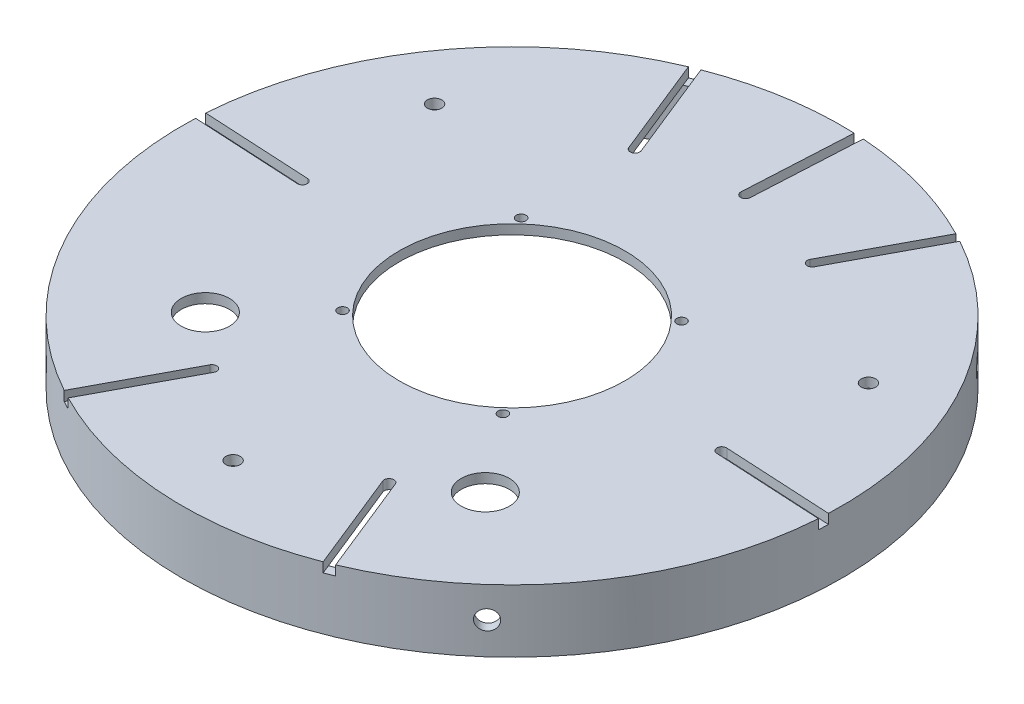
SolidWorks part; units mm, degrees
material "6061 Alloy"
ref_plane "Front Plane" through (0, 0, 0) normal (0, 0, 1) x (1, 0, 0)
ref_plane "Top Plane" through (0, 0, 0) normal (0, 1, 0) x (1, 0, 0)
ref_plane "Right Plane" through (0, 0, 0) normal (1, 0, 0) x (0, 0, -1)
sketch "Sketch1" plane through (0, 0, 0) normal (0, 1, 0) x (-0.9986, 0, -0.0535)
  line L0 (55.4987, 41.0091) -> (55.4987, 34.0091) construction
  line L2 (55.4987, -32.3449) -> (55.4987, -2.3278) construction
  circle A1 centre (55.4987, -32.3449) radius 68.37
  circle A3 centre (55.4987, -32.3449) radius 23.401
extrude "Boss-Extrude1" add sketch "Sketch1" along normal blind 2
sketch "Sketch3" plane through (0, 2, 0) normal (0, 1, 0) x (1, 0, 0)
  circle A0 centre (-53.6871, 35.2703) radius 68.37
  circle A1 centre (-53.6871, 35.2703) radius 66.37
extrude "Boss-Extrude2" add sketch "Sketch3" against normal blind 13
sketch "Sketch24" [suppressed] plane through (0, 4.3, 0) normal (0, 1, 0) x (1, 0, 0)
  line L0 (-34.4111, 2.0274) -> (-34.9466, -7.9582) construction
  line L1 (25.902, -11.2211) -> (26.4375, -1.2355) construction
  point P0 (-34.6788, -2.9654)
  point P1 (26.1698, -6.2283)
sketch "Sketch25" [suppressed] plane through (0, 0, 0) normal (0, -1, 0) x (1, 0, 0)
  point P0 (-34.6788, 2.9654)
  point P1 (26.1698, 6.2283)
ref_plane "Plane1" [suppressed] through (-0.258, 0, 4.8112) normal (0.0535, 0, -0.9986) x (-0.9986, 0, -0.0535)
sketch "Sketch29" [suppressed] plane through (0, 4.3, 0) normal (0, 1, 0) x (1, 0, 0)
  arc A0 (18.841, -0.8281) -> (-26.8146, 1.6201) centre (-4.2545, -4.5968) ccw construction
  arc A1 (-27.3501, -8.3656) -> (18.3055, -10.8138) centre (-4.2545, -4.5968) ccw construction
  point P0 (-3.0015, 18.7706)
  point P1 (-5.5076, -27.9643)
sketch "Sketch30" [suppressed] plane through (0, 0, 0) normal (0, -1, 0) x (1, 0, 0)
  point P0 (-5.5076, 27.9643)
  point P1 (-3.0015, -18.7706)
ref_plane "Plane2" [suppressed] through (-3.9965, 0, -0.2143) normal (-0.9986, 0, -0.0535) x (-0.0535, 0, 0.9986)
sketch "Sketch35" [suppressed] plane through (0, 0, 0) normal (0, 1, 0) x (1, 0, 0)
  line L0 (-3.8699, 2.5759) -> (-4.1232, -2.1473) construction
  line L1 (2.1036, -4.9378) -> (-2.6196, -4.6845) construction
  line L2 (20.5267, 17.662) -> (-4.2545, -4.5968) construction
  line L3 (-4.2545, -4.5968) -> (-31.1135, -28.7219) construction
  arc A1 (-27.3501, -8.3656) -> (18.3055, -10.8138) centre (-4.2545, -4.5968) ccw construction
  point P0 (-4.2545, -4.5968)
  point P8 (20.5267, 17.662)
  point P10 (-21.6638, -20.2341)
sketch "Sketch36" [suppressed] plane through (0, 4.3, 0) normal (0, 1, 0) x (1, 0, 0)
  point P0 (20.5267, 17.662)
ref_plane "Plane3" [suppressed] through (0.3855, 0, 0.4291) normal (0.6682, 0, 0.744) x (0.744, 0, -0.6682)
sketch "Sketch37" [suppressed] plane through (0, 4.3, 0) normal (0, 1, 0) x (1, 0, 0)
  line L1 (-26.6296, 20.3138) -> (-4.2545, -4.5968) construction
  line L2 (-4.2545, -4.5968) -> (20.7564, -32.4421) construction
  point P0 (-4.2545, -4.5968)
  point P7 (-26.6296, 20.3138)
sketch "Sketch39" [suppressed] plane through (0, 0, 0) normal (0, -1, 0) x (1, 0, 0)
  point P0 (-26.6296, -20.3138)
ref_plane "Plane4" [suppressed] through (-4.64, 0, 4.1677) normal (-0.744, 0, 0.6682) x (0.6682, 0, 0.744)
sketch "Sketch40" [suppressed] plane through (0.3855, 0, 0.4291) normal (0.6682, 0, 0.744) x (0.744, 0, -0.6682)
  circle A0 centre (-6.2369, -3.85) radius 2
extrude "Cut-Extrude27" [suppressed] cut sketch "Sketch40" against normal through all
pattern_circular "CirPattern2" [suppressed] count 4 over 360
sketch "Sketch58" plane through (0, 2, 0) normal (0, 1, 0) x (1, 0, 0)
  line L2 (-12.7238, 29.0656) -> (-12.2954, 37.0565)
  line L3 (-12.2954, 37.0565) -> (-7.3025, 36.7887)
  line L4 (-7.3025, 36.7887) -> (-7.731, 28.7979)
  line L5 (-7.731, 28.7979) -> (-12.7238, 29.0656)
sketch "Sketch60" plane through (0, 2, 0) normal (0, 1, 0) x (1, 0, 0)
  line L0 (-52.2437, 62.1872) -> (-55.1305, 8.3534) construction
  line L1 (-84.1539, 36.904) -> (-23.2203, 33.6365) construction
  line L4 (-73.7408, 17.2578) -> (-104.5394, -10.4059) construction
  line L5 (-53.6871, 35.2703) -> (-73.7408, 17.2578) construction
  line L6 (-71.6996, 55.324) -> (-99.3633, 86.1226) construction
  line L7 (-53.6871, 35.2703) -> (-71.6996, 55.324) construction
  line L8 (-33.6334, 53.2828) -> (-2.8348, 80.9464) construction
  line L9 (-53.6871, 35.2703) -> (-33.6334, 53.2828) construction
  line L10 (-35.6746, 15.2165) -> (-8.0109, -15.5821) construction
  line L11 (-53.6871, 35.2703) -> (-35.6746, 15.2165) construction
  line L12 (-73.7408, 17.2578) -> (-104.5394, -10.4059) construction
  line L13 (-53.6871, 35.2703) -> (-73.7408, 17.2578) construction
  arc A1 (-55.1305, 8.3534) -> (-80.604, 36.7136) centre (-53.6871, 35.2703) cw
  dimension "D1" = 4
sketch "Sketch62" plane through (0, 0, 0) normal (0, -1, 0) x (1, 0, 0)
  line L0 (-8.0109, 15.5821) -> (-99.3633, -86.1226) construction
  line L1 (-104.5394, 10.4059) -> (-2.8348, -80.9464) construction
  point P9 (-53.6871, -35.2703)
ref_plane "Plane5" through (-41.5069, 0, -46.2106) normal (0.6682, 0, 0.744) x (0.744, 0, -0.6682)
ref_plane "Plane6" through (-12.1802, 0, 10.9404) normal (0.744, 0, -0.6682) x (-0.6682, 0, -0.744)
sketch "Sketch63" plane through (-41.5069, 0, -46.2106) normal (0.6682, 0, 0.744) x (0.744, 0, -0.6682)
  line L0 (-84.7262, 0) -> (51.9818, 0) construction
  line L3 (-16.3722, 0) -> (-16.3722, -8.7) construction
  circle A0 centre (-16.3722, -4.35) radius 2
extrude "Cut-Extrude40" cut sketch "Sketch63" against normal through all and the other way through all
sketch "Sketch64" plane through (-12.1802, 0, 10.9404) normal (0.744, 0, -0.6682) x (-0.6682, 0, -0.744)
  line L0 (-6.2392, 0) -> (130.4688, 0) construction
  line L3 (62.1148, 0) -> (62.1148, -8.7) construction
  circle A0 centre (62.1148, -4.35) radius 2
extrude "Cut-Extrude41" cut sketch "Sketch64" against normal through all and the other way through all
sketch "Sketch65" plane through (0, 2, 0) normal (0, -1, 0) x (1, 0, 0)
  line L2 (1.1947, -31.5296) -> (-6.7555, -31.9265)
  line L3 (0.4048, -1118.9656) -> (-50.8954, -91.2006) construction
  line L4 (1.2944, -33.5271) -> (-6.7555, -33.9289)
  line L5 (-108.5689, -39.0109) -> (-100.6187, -38.6141)
  line L6 (-108.6686, -37.0134) -> (-100.6187, -36.6116)
  line L7 (-49.9465, -90.152) -> (-50.3433, -82.2019)
  line L8 (-51.944, -90.2517) -> (-52.3458, -82.2019)
  line L16 (-57.4277, 19.6115) -> (-57.0309, 11.6614) [skipped]
  line L17 (-55.4302, 19.7112) -> (-55.0284, 11.6614) [skipped]
  arc A2 (1.2944, -33.5271) -> (1.1947, -31.5296) centre (1.2445, -32.5284) ccw
  arc A3 (-6.7555, -33.9289) -> (-6.7555, -31.9265) centre (-6.8055, -32.9277) cw
  arc A4 (-51.944, -90.2517) -> (-49.9465, -90.152) centre (-50.9452, -90.2019) ccw
  arc A5 (-52.3458, -82.2019) -> (-50.3433, -82.2019) centre (-51.3445, -82.1519) cw
  arc A6 (-108.6686, -37.0134) -> (-108.5689, -39.0109) centre (-108.6187, -38.0121) ccw
  arc A7 (-100.6187, -36.6116) -> (-100.6187, -38.6141) centre (-100.5687, -37.6128) cw
  arc A16 (-55.4302, 19.7112) -> (-57.4277, 19.6115) centre (-56.429, 19.6614) ccw [skipped]
  arc A17 (-55.0284, 11.6614) -> (-57.0309, 11.6614) centre (-56.0297, 11.6114) cw [skipped]
  dimension "D1" = 4
sketch "Sketch67" plane through (0, 2, 0) normal (0, 1, 0) x (1, 0, 0)
  line L0 (-99.6611, 37.7404) -> (-7.7126, 32.8099) construction
  line L1 (-51.2218, 81.2445) -> (-56.1524, -10.704) construction
  line L2 (-47.8311, 125.7094) -> (-49.8283, 125.8165)
  line L3 (-144.1262, 41.1262) -> (-144.2333, 39.1291)
  line L4 (-99.6075, 38.739) -> (-144.1262, 41.1262)
  line L5 (-99.7146, 36.7419) -> (-144.2333, 39.1291)
  line L6 (-50.2184, 81.1907) -> (-47.8311, 125.7094)
  line L7 (-52.2155, 81.2978) -> (-49.8283, 125.8165)
  line L8 (36.752, 29.4143) -> (36.8591, 31.4114)
  line L9 (-7.7667, 31.8015) -> (36.752, 29.4143)
  line L10 (-7.6596, 33.7987) -> (36.8591, 31.4114)
  line L49 (-59.5431, -55.1689) -> (-57.5459, -55.276) [skipped]
  line L50 (-57.1558, -10.6501) -> (-59.5431, -55.1689) [skipped]
  line L51 (-55.1587, -10.7572) -> (-57.5459, -55.276) [skipped]
  arc A1 (-99.6075, 38.739) -> (-99.7146, 36.7419) centre (-99.6611, 37.7404) cw
  arc A2 (-50.2184, 81.1907) -> (-52.2155, 81.2978) centre (-51.2169, 81.2442) cw
  arc A3 (-7.7667, 31.8015) -> (-7.6596, 33.7987) centre (-7.7132, 32.8001) cw
  arc A8 (-57.1558, -10.6501) -> (-55.1587, -10.7572) centre (-56.1573, -10.7037) cw [skipped]
  dimension "D1" = 4
extrude "Cut-Extrude45" cut sketch "Sketch67" against normal blind 2
sketch "Sketch70" plane through (0, 2, 0) normal (0, 1, 0) x (1, 0, 0)
  line L0 (-51.2169, 81.2442) -> (-53.6871, 35.2703) construction
  line L1 (-99.6611, 37.7404) -> (-7.7132, 32.8001) construction
  line L2 (-53.6871, 35.2703) -> (-56.5307, -17.6534) construction
  circle A0 centre (-99.7745, 65.2862) radius 1.5
  circle A1 centre (-56.638, -19.6505) radius 1.5
  circle A2 centre (-4.6489, 60.1751) radius 1.5
  dimension "D1" = 3
  dimension "D2" = 3
sketch "Sketch72" plane through (0, 2, 0) normal (0, 1, 0) x (1, 0, 0)
  line L0 (-51.2169, 81.2442) -> (-56.638, -19.6505) construction
  line L1 (-99.6611, 37.7404) -> (-7.7132, 32.8001) construction
sketch "Sketch73" plane through (0, 2, 0) normal (0, -1, 0) x (1, 0, 0)
  circle A0 centre (-72.2141, -18.6326) radius 1
  circle A1 centre (-37.0495, -16.7433) radius 1
  circle A2 centre (-35.1601, -51.9079) radius 1
  circle A3 centre (-70.3247, -53.7973) radius 1
extrude "Cut-Extrude47" cut sketch "Sketch73" along normal blind 10
extrude "Cut-Extrude48" cut sketch "Sketch70" against normal blind 10
extrude "Cut-Extrude49" cut sketch "Sketch74" against normal blind 10
sketch "Sketch74" plane through (19.5625, 3, -2.0536) normal (0, 1, 0) x (1, 0, 0)
  line L0 (-73.2496, 33.2167) -> (-76.2005, -21.7041) construction
  line L1 (-73.2496, 33.2167) -> (-44.3242, -1.2553) construction
  line L2 (-73.2496, 33.2167) -> (-105.7022, 2.0425) construction
  circle A0 centre (-105.7022, 2.0425) radius 5
  circle A1 centre (-44.3242, -1.2553) radius 5
sketch "Sketch75" plane through (0, 2, 0) normal (0, 1, 0) x (1, 0, 0)
  line L0 (-50.0757, 102.5274) -> (-51.2185, 81.2443) construction
  line L1 (-120.9442, 38.8817) -> (13.57, 31.6588) construction
  line L2 (-86.2666, -23.6885) -> (-88.9936, -28.8014)
  line L3 (-22.8723, 95.1703) -> (-32.9078, 76.3546)
  line L4 (-21.1076, 94.229) -> (-31.1431, 75.4134)
  line L5 (-88.9936, -28.8014) -> (-87.2289, -29.7426)
  line L6 (-53.5602, 37.6331) -> (-58.8341, -60.585) construction
  line L7 (-52.5853, 35.2111) -> (-52.8048, 34.7997)
  line L8 (-84.5019, -24.6297) -> (-87.2289, -29.7426)
  line L9 (-79.7658, 97.3787) -> (-83.5737, 106.8386)
  line L10 (-53.5602, 37.6331) -> (-54.5694, 35.7409)
  line L11 (-77.9105, 98.1256) -> (-82.0529, 108.4166)
  line L12 (-79.7658, 97.3787) -> (-71.8029, 77.5967)
  line L13 (-22.8723, 95.1703) -> (-17.9091, 104.4757)
  line L14 (-77.9105, 98.1256) -> (-69.9475, 78.3435)
  line L15 (-27.6084, -26.8382) -> (-35.5714, -7.0562)
  line L16 (-21.1076, 94.229) -> (-18.0109, 100.0352)
  line L17 (-29.4638, -27.5851) -> (-37.4267, -7.803)
  line L18 (-29.4638, -27.5851) -> (-27.0828, -33.5)
  line L19 (-84.5019, -24.6297) -> (-74.4664, -5.8141)
  line L20 (-86.2666, -23.6885) -> (-76.2311, -4.8729)
  line L21 (-27.6084, -26.8382) -> (-25.2275, -32.7531)
  line L22 (-25.2275, -32.7531) -> (-27.0828, -33.5)
  line L23 (-83.5737, 106.8386) -> (-82.0529, 108.4166)
  line L24 (-17.9091, 104.4757) -> (-18.0109, 100.0352)
  arc A3 (-32.9078, 76.3546) -> (-31.1431, 75.4134) centre (-32.0254, 75.884) ccw
  arc A4 (-69.9475, 78.3435) -> (-71.8029, 77.5967) centre (-70.8752, 77.9701) cw
  arc A5 (-37.4267, -7.803) -> (-35.5714, -7.0562) centre (-36.499, -7.4296) cw
  arc A6 (-74.4664, -5.8141) -> (-76.2311, -4.8729) centre (-75.3488, -5.3435) ccw
extrude "Cut-Extrude51" cut sketch "Sketch75" against normal blind 2
